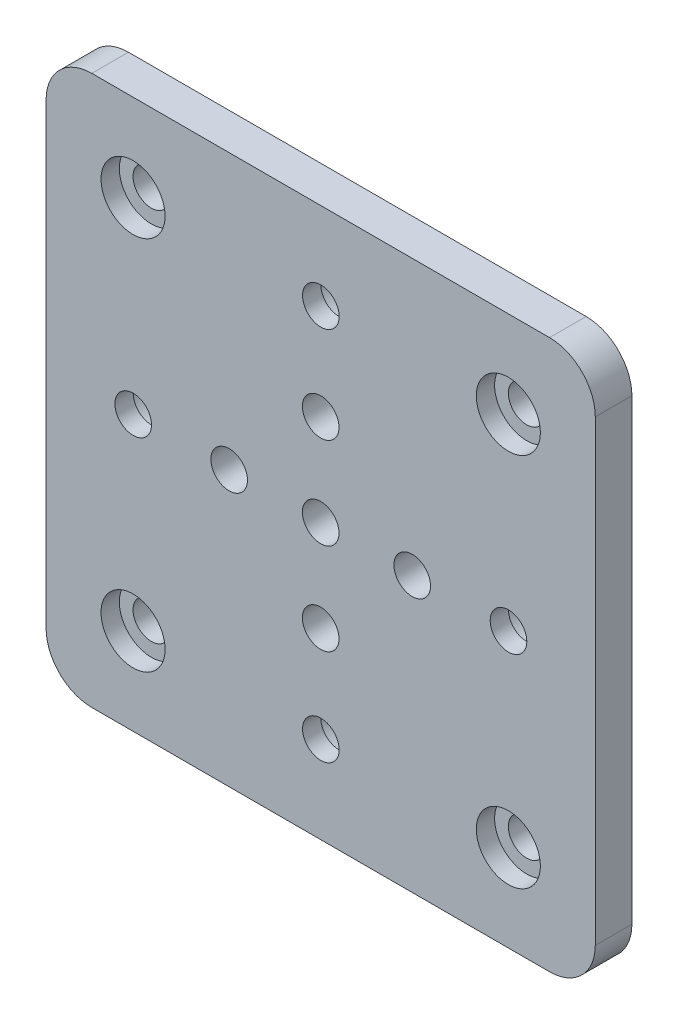
SolidWorks part; units mm, degrees
ref_plane "Front Plane" through (0, 0, 0) normal (0, 0, 1) x (1, 0, 0)
ref_plane "Top Plane" through (0, 0, 0) normal (0, 1, 0) x (1, 0, 0)
ref_plane "Right Plane" through (0, 0, 0) normal (1, 0, 0) x (0, 0, -1)
sketch "Sketch1" plane through (0, 0, 0) normal (0, 0, 1) x (1, 0, 0)
  line L1 (29.9829, -25) -> (29.9829, 25)
  line L2 (24.9829, 30) -> (-25.0171, 30)
  line L3 (-30.0171, 25) -> (-30.0171, -25)
  line L4 (-25.0171, -30) -> (24.9829, -30)
  circle A0 centre (-20.5171, 20.5) radius 2
  circle A1 centre (-10.0171, 0) radius 2
  circle A2 centre (-0.0171, 0) radius 2
  circle A6 centre (20.4829, -20.5) radius 2
  circle A7 centre (0, 20.5) radius 2
  circle A8 centre (20.4829, 20.5) radius 2
  circle A9 centre (-20.5171, -20.5) radius 2
  circle A10 centre (-0.0171, 10) radius 2
  circle A11 centre (9.9829, 0) radius 2
  circle A12 centre (-0.0171, -10) radius 2
  circle A13 centre (20.5, 0) radius 2
  circle A14 centre (0, -20.5) radius 2
  circle A15 centre (-20.5, 0) radius 2
  arc A16 (24.9829, -30) -> (29.9829, -25) centre (24.9829, -25) ccw
  arc A17 (29.9829, 25) -> (24.9829, 30) centre (24.9829, 25) ccw
  arc A18 (-25.0171, 30) -> (-30.0171, 25) centre (-25.0171, 25) ccw
  arc A19 (-30.0171, -25) -> (-25.0171, -30) centre (-25.0171, -25) ccw
  point P10 (0, 0)
  point P36 (-0.0171, 0)
other "AlignGroup1"
other "AlignGroup2" parameters "D2"=5, "D3"=5, "D4"=5, "D1"=0, "D5"=10, "D6"=10, "D7"=14.1421, "D8"=28.9914, "D9"=20.5, "D10"=20.5, "D11"=20.5171, "D12"=30.0171, "D13"=10, "D14"=20.5, "D15"=30, "D16"=10, "D17"=20.5, "D18"=30
extrude "Boss-Extrude2" add sketch "Sketch1" along normal blind 4
sketch "Sketch2" plane through (0, 0, 4) normal (0, 0, 1) x (1, 0, 0)
  circle A2 centre (-20.5171, 20.5) radius 3.5
  circle A3 centre (-20.5171, 20.5) radius 3.5
  circle A5 centre (-20.5171, -20.5) radius 3.5
  circle A6 centre (-20.5171, -20.5) radius 3.5
  circle A8 centre (20.4829, -20.5) radius 3.5
  circle A9 centre (20.4829, -20.5) radius 3.5
  circle A11 centre (20.4829, 20.5) radius 3.5
  circle A12 centre (20.4829, 20.5) radius 3.5
  dimension "D1" = 1.5
  dimension "D2" = 1.5
  dimension "D3" = 1.5
  dimension "D4" = 1.5
extrude "Cut-Extrude1" cut sketch "Sketch2" against normal blind 2
sketch "Sketch3" plane through (0, 0, 0) normal (0, 0, -1) x (-1, 0, 0)
  circle A2 centre (-20.5, 0) radius 3.5
  circle A3 centre (-20.5, 0) radius 3.5
  circle A5 centre (20.5, 0) radius 3.5
  circle A6 centre (20.5, 0) radius 3.5
  circle A8 centre (0, 20.5) radius 3.5
  circle A9 centre (0, 20.5) radius 3.5
  circle A11 centre (0, -20.5) radius 3.5
  circle A12 centre (0, -20.5) radius 3.5
  dimension "D1" = 1.5
  dimension "D2" = 1.5
  dimension "D3" = 1.5
  dimension "D4" = 1.5
extrude "Cut-Extrude2" cut sketch "Sketch3" against normal blind 2
